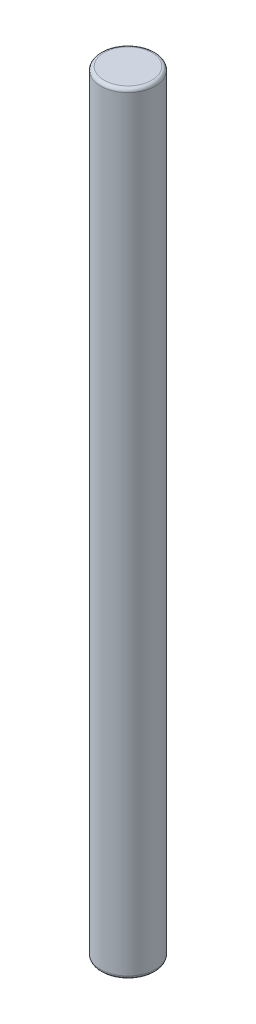
SolidWorks part; units mm, degrees
ref_plane "Front Plane" through (0, 0, 0) normal (0, 0, 1) x (1, 0, 0)
ref_plane "Top Plane" through (0, 0, 0) normal (0, 1, 0) x (1, 0, 0)
ref_plane "Right Plane" through (0, 0, 0) normal (1, 0, 0) x (0, 0, -1)
sketch "Sketch1" plane through (0, 0, 0) normal (0, 1, 0) x (1, 0, 0)
  circle A0 centre (0, 0) radius 4
  dimension "D1" = 8
extrude "Boss-Extrude1" add sketch "Sketch1" along normal blind 113
fillet "Fillet1" radius 0.5 1 edges at (0, 113, 4)
fillet "Fillet2" radius 0.5 1 edges at (0, 0, 4)
